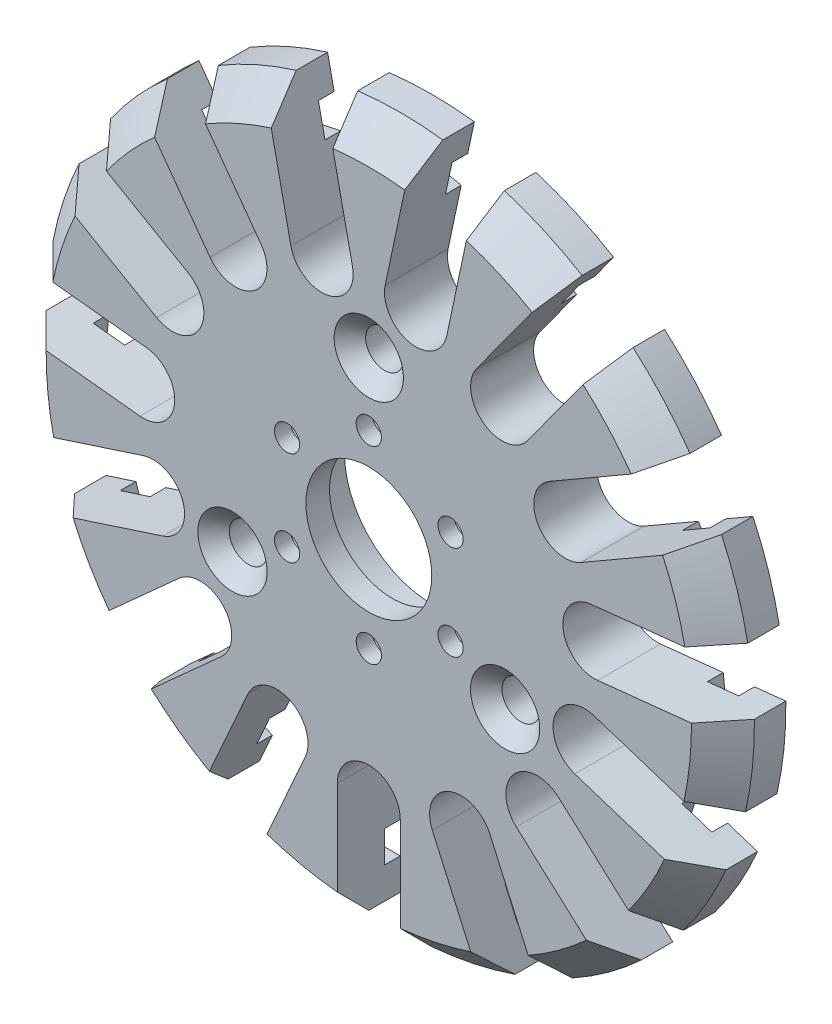
SolidWorks part; units mm, degrees
material "Liga 1060"
ref_plane "Plano frontal" through (0, 0, 0) normal (0, 0, 1) x (1, 0, 0)
ref_plane "Plano superior" through (0, 0, 0) normal (0, 1, 0) x (1, 0, 0)
ref_plane "Plano direito" through (0, 0, 0) normal (1, 0, 0) x (0, 0, -1)
sketch "Esboço1" plane through (0, 0, 0) normal (0, 0, 1) x (1, 0, 0)
  circle A0 centre (0, 0) radius 22.5
  dimension "D1" = 45
extrude "Ressalto-extrusão1" add sketch "Esboço1" along normal blind 4
chamfer "Chanfro1" distance 2 angle 45 1 edges at (22.5, 0, 4)
sketch "Esboço4" plane through (0, 0, 0) normal (0, 0, -1) x (-1, 0, 0)
  circle A0 centre (0, 0) radius 5.55
  dimension "D1" = 11.1
extrude "Corte-extrusão2" cut sketch "Esboço4" against normal blind 2.5 contours A0
sketch "Esboço5" plane through (0, 0, 2.5) normal (0, 0, -1) x (-1, 0, 0)
  circle A0 centre (0, 0) radius 4
  dimension "D1" = 8
extrude "Corte-extrusão3" cut sketch "Esboço5" against normal blind 2
sketch "Esboço6" plane through (0, 0, 0) normal (0, 0, -1) x (-1, 0, 0)
  line L0 (0, 0) -> (0, -22.5) construction
  line L1 (2, -22.4109) -> (2, -14.4109)
  line L2 (-2, -14.4109) -> (-2, -22.4109)
  circle A0 centre (0, 0) radius 22.5 construction
  arc A1 (-2, -22.4109) -> (2, -22.4109) centre (0, 0) ccw
  arc A2 (2, -14.4109) -> (-2, -14.4109) centre (0, -14.4109) ccw
  dimension "D1" = 4
  dimension "D2" = 8
extrude "Corte-extrusão4" cut sketch "Esboço6" against normal blind 4
pattern_circular "PadrãoCircular1" count 15 over 360 about axis through (0, 0, 0) along (0, 0, 1) of "Corte-extrusão4"
sketch "Esboço8" plane through (0, 0, 0) normal (0, 0, -1) x (-1, 0, 0)
  circle A0 centre (0, 0) radius 20.5
  circle A1 centre (0, 0) radius 18.5
  dimension "D1" = 41
  dimension "D2" = 37
sketch "Esboço9" plane through (0, 0, 4) normal (0, 0, 1) x (1, 0, 0)
  circle A0 centre (0, 0) radius 6
  circle A1 centre (0, 0) radius 4
  circle A2 centre (0, 0) radius 10
  point P4 (0, 6)
  point P6 (0, 10)
  dimension "D1" = 8
  dimension "D2" = 12
  dimension "D3" = 20
hole_wizard "Broca de rosquear para tarraxa de M21" positions "3DSketch1" profile "Esboço10" hole size "M2" standard "ISO"
sketch3d "3DSketch1"
  point P0 (0, 6, 4)
sketch "Esboço10" plane through (0, 6, 4) normal (1, 0, 0) x (0, -1, 0)
  line L0 (0, 0) -> (0, 1.5)
  line L1 (0, 1.5) -> (0.8, 1.0193)
  line L2 (0.8, 1.0193) -> (0.8, 0)
  line L5 (0.8, 0) -> (0, 0)
  line L10 (0, 1.5) -> (-0.8, 1.0193) construction
  line L11 (0, -6.35) -> (0, 107.95) construction
  dimension "Hole Dia." = 1.6
  dimension "Hole Depth" = 1.5
  dimension "Drill Angle" = 118
hole_wizard "Escareado para parafuso com cabeça escareada chata de M21" positions "3DSketch2" profile "Esboço14" countersink size "M2" standard "ISO" end condition through all
sketch3d "3DSketch2"
  point P0 (0, 10, 4)
sketch "Esboço14" plane through (0, 10, 4) normal (1, 0, 0) x (0, -1, 0)
  line L0 (0, 0) -> (0, 4)
  line L1 (0, 4) -> (1.2, 4)
  line L2 (1.2, 4) -> (1.2, 1)
  line L3 (1.2, 1) -> (2.2, 0)
  line L5 (2.2, 0) -> (0, 0)
  line L6 (-1.2, 1) -> (-2.2, 0) construction
  line L11 (0, -6.35) -> (0, 107.95) construction
  dimension "Thru Hole Dia." = 2.4
  dimension "Thru Hole Depth" = 4
  dimension "Near C'Sink Dia." = 4.4
  dimension "Near C'Sink Angle" = 90
pattern_circular "PadrãoCircular2" count 6 over 360 about axis through (0, 0, 0) along (0, 0, 1) of "Broca de rosquear para tarraxa de M21"
sketch "Esboço12" plane through (0, 0, 0) normal (0, 0, -1) x (-1, 0, 0)
  line L2 (3.5, -20.4109) -> (-3.5, -20.4109)
  line L3 (-3.5, -20.4109) -> (-3.5, -18.4109)
  line L4 (-3.5, -18.4109) -> (3.5, -18.4109)
  line L5 (3.5, -18.4109) -> (3.5, -20.4109)
  line L6 (0, 0) -> (0, -22.5) construction
  arc A0 (-7.2883, -21.2869) -> (-2, -22.4109) centre (0, 0) ccw construction
  point P0 (0, -18.4109)
  dimension "D1" = 2
  dimension "D2" = 7
  dimension "D3" = 2
extrude "Corte-extrusão5" cut sketch "Esboço12" against normal blind 1
pattern_circular "PadrãoCircular3" count 15 over 360 about axis through (0, 0, 0) along (0, 0, 1) of "Corte-extrusão5"
pattern_circular "PadrãoCircular4" count 3 over 360 about axis through (0, 0, 0) along (0, 0, 1) of "Escareado para parafuso com cabeça escareada chata de M21"
